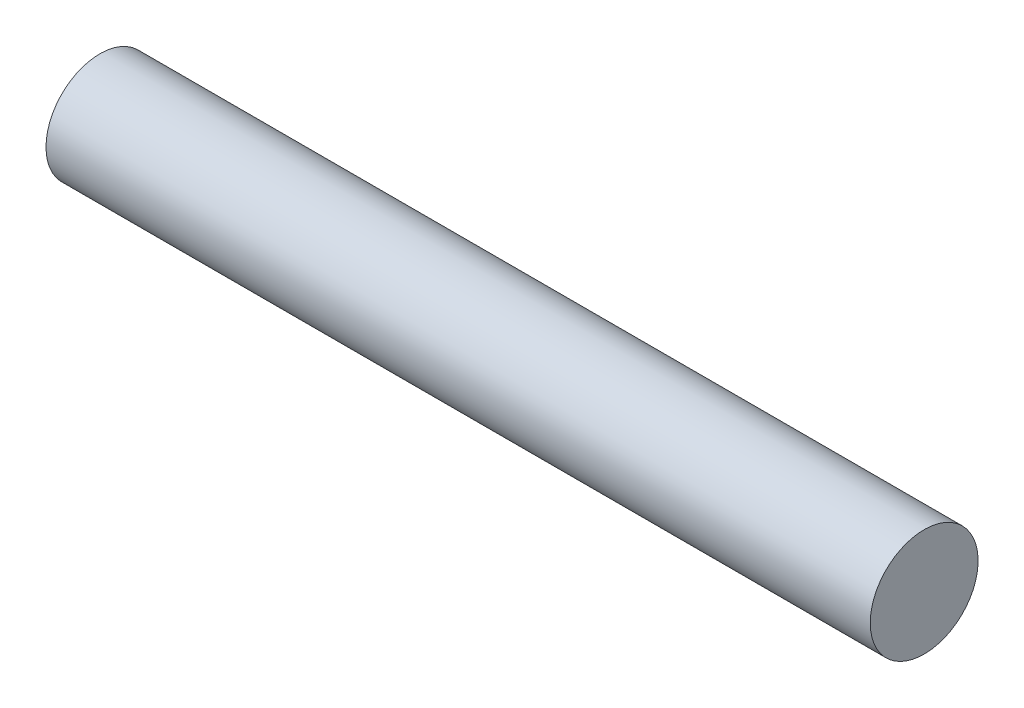
SolidWorks part; units mm, degrees
ref_plane "前视基准面" through (0, 0, 0) normal (0, 0, 1) x (1, 0, 0)
ref_plane "上视基准面" through (0, 0, 0) normal (0, 1, 0) x (1, 0, 0)
ref_plane "右视基准面" through (0, 0, 0) normal (1, 0, 0) x (0, 0, -1)
other "Configuration Table"
sketch "草图1" plane through (0, 0, 0) normal (0, 0, 1) x (1, 0, 0)
  line L0 (0, 0) -> (40.0305, 0) construction
  line L1 (0, 0) -> (0, 7)
  line L2 (0, 7) -> (107, 7)
  line L3 (107, 7) -> (107, 0)
  line L4 (0, 0) -> (107, 0)
  dimension "D1" = 7
  dimension "D2" = 107
revolve "旋转1" add sketch "草图1" angle 360 about L0
